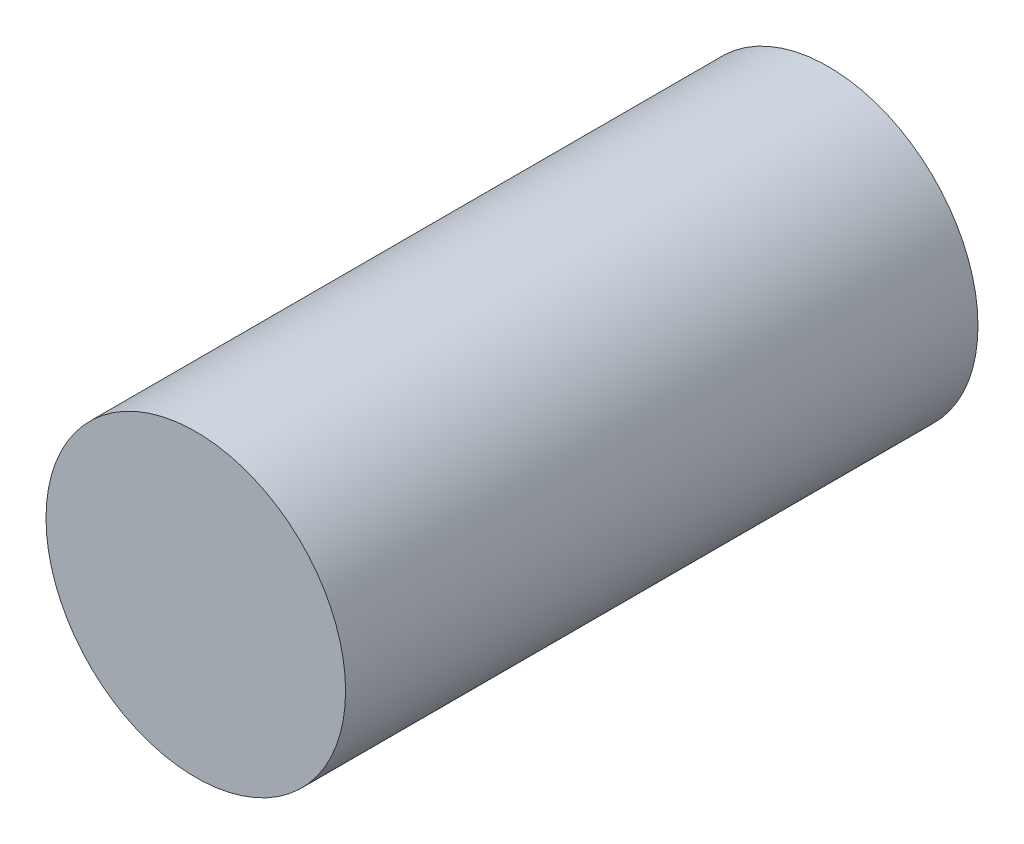
SolidWorks part; units mm, degrees
ref_plane "前视基准面" through (0, 0, 0) normal (0, 0, 1) x (1, 0, 0)
ref_plane "上视基准面" through (0, 0, 0) normal (0, 1, 0) x (1, 0, 0)
ref_plane "右视基准面" through (0, 0, 0) normal (1, 0, 0) x (0, 0, -1)
sketch "草图1" plane through (0, 0, 0) normal (0, 0, 1) x (1, 0, 0)
  circle A0 centre (0, 0) radius 4.5
  dimension "D1" = 9
extrude "凸台-拉伸1" add sketch "草图1" along normal blind 19
